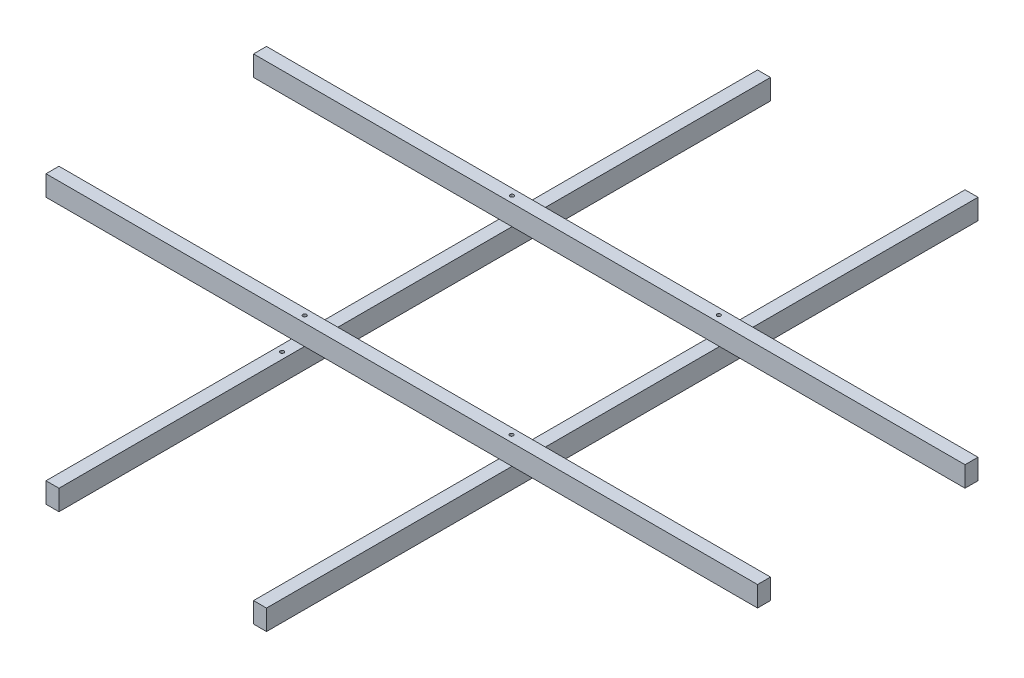
SolidWorks part; units mm, degrees
material "Doug Fir"
ref_plane "Front Plane" through (0, 0, 0) normal (0, 0, 1) x (1, 0, 0)
ref_plane "Top Plane" through (0, 0, 0) normal (0, 1, 0) x (1, 0, 0)
ref_plane "Right Plane" through (0, 0, 0) normal (1, 0, 0) x (0, 0, -1)
sketch "Lower Level" plane through (0, 0, 0) normal (0, 1, 0) x (1, 0, 0)
  line L0 (1422.4, 0) -> (1422.4, 4876.8)
  line L1 (2844.8, 0) -> (2844.8, 4876.8)
  line L2 (1422.4, 2438.4) -> (2844.8, 2438.4) construction
  point P7 (2133.6, 2438.4)
  dimension "D1" = 4876.8
  dimension "D2" = 711.2
ref_plane "Plane2" through (0, 139.7, 0) normal (0, 1, 0) x (1, 0, 0)
sketch "Sketch12" plane through (0, 139.7, 0) normal (0, 1, 0) x (1, 0, 0)
  line L0 (-304.8, 3149.6) -> (4572, 3149.6)
  line L1 (4572, 1727.2) -> (-304.8, 1727.2)
  line L2 (2133.6, 3149.6) -> (2133.6, 1727.2) construction
  point P0 (2133.6, 2438.4)
  point P6 (2133.6, 1727.2)
  point P7 (2133.6, 3149.6)
  point P10 (2133.6, 2438.4)
  dimension "D1" = 4876.8
  dimension "D2" = 711.2
other "Profiles 4X6(1)"
ref_plane "Plane1" through (1422.4, 0, 0) normal (0, 0, -1) x (-1, 0, 0)
sketch "Sketch1" plane through (1422.4, 0, 0) normal (0, 0, -1) x (-1, 0, 0)
  line L1 (-44.45, 69.85) -> (44.45, 69.85)
  line L2 (-44.45, 69.85) -> (-44.45, -69.85)
  line L3 (-44.45, -69.85) -> (44.45, -69.85)
  line L4 (44.45, 69.85) -> (44.45, -69.85)
  line L5 (-44.45, 69.85) -> (44.45, -69.85) construction
  line L6 (-44.45, -69.85) -> (44.45, 69.85) construction
  point P0 (0, 0)
  point P6 (0, 69.85)
  point P7 (0, -69.85)
  point P8 (44.45, 0)
  point P9 (-44.45, 0)
  point P10 (0, 0)
  dimension "D1" = 88.9
  dimension "D2" = 139.7
sketch3d "3DSketch2"
  line L0 (2133.6, 139.7, -2438.4) -> (2133.6, 0, -2438.4)
  line L1 (1422.4, 0, -2438.4) -> (2844.8, 0, -2438.4) construction
sketch "Sketch13" plane through (0, 209.55, 0) normal (0, 1, 0) x (1, 0, 0)
  line L0 (1422.4, 0) -> (1422.4, 4876.8) construction
  line L1 (-304.8, 3149.6) -> (4572, 3149.6) construction
  circle A0 centre (1422.4, 3149.6) radius 12.7
  circle A1 centre (2840.2576, 3149.6) radius 12.7
  circle A2 centre (1422.4, 1728.393) radius 12.7
  circle A3 centre (2840.2576, 1728.393) radius 12.7
  dimension "D1" = 25.4
extrude "Cut-Extrude1" cut sketch "Sketch13" against normal through all
sketch "Sketch15" plane through (0, 69.85, 0) normal (0, 1, 0) x (1, 0, 0)
  circle A0 centre (1422.1961, 1574.2617) radius 12.7
  circle A1 centre (1422.1961, 3186.4746) radius 12.7
  dimension "D1" = 25.4
  dimension "D2" = 25.4
extrude "Cut-Extrude5" cut sketch "Sketch15" against normal through all
equation "\"Width\" = 28"
equation "\"Length\"=192"
equation "\"D1@Lower Level\"=\"Length\""
equation "\"D2@Lower Level\"=\"Width\""
equation "\"D1@Sketch12\"=\"Length\""
equation "\"D2@Sketch12\"=\"Width\""
